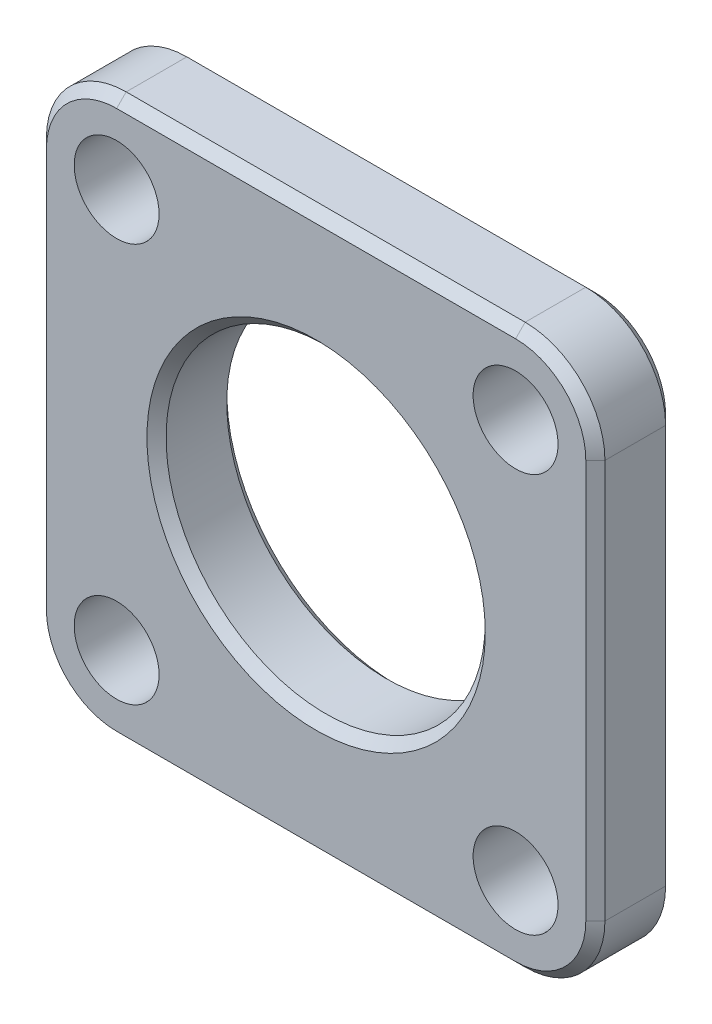
SolidWorks part; units mm, degrees
material "AISI 1020"
ref_plane "Front Plane" through (0, 0, 0) normal (0, 0, 1) x (1, 0, 0)
ref_plane "Top Plane" through (0, 0, 0) normal (0, 1, 0) x (1, 0, 0)
ref_plane "Right Plane" through (0, 0, 0) normal (1, 0, 0) x (0, 0, -1)
sketch "Base Sketch" plane through (0, 0, 0) normal (0, 0, 1) x (1, 0, 0)
  line L1 (22.225, -22.225) -> (-22.225, -22.225)
  line L2 (22.225, -22.225) -> (22.225, 22.225)
  line L3 (22.225, 22.225) -> (-22.225, 22.225)
  line L4 (-22.225, -22.225) -> (-22.225, 22.225)
  line L5 (22.225, -22.225) -> (-22.225, 22.225) construction
  line L6 (22.225, 22.225) -> (-22.225, -22.225) construction
  circle A0 centre (0, 0) radius 12.7
  point P0 (0, 0)
  dimension "D3" = 25.4
  dimension "D1" = 44.45
  dimension "D2" = 44.45
extrude "Base Extrude" add sketch "Base Sketch" against normal blind 6.35
fillet "Corner Fillet" radius 6.35 4 edges at (-22.225, -22.225, -3.175) (-22.225, 22.225, -3.175) (22.225, -22.225, -3.175) (22.225, 22.225, -3.175)
chamfer "Peripheral Chamfer" distance 0.762 angle 45 18 edges at (20.3651, -20.3651, -6.35) (22.225, 0, -6.35) (20.3651, 20.3651, -6.35) (0, 22.225, -6.35) (-20.3651, 20.3651, -6.35) (-22.225, 0, -6.35) (-20.3651, -20.3651, -6.35) (0, -22.225, -6.35) (12.7, 0, -6.35) (-20.3651, 20.3651, 0) (0, 22.225, 0) (20.3651, 20.3651, 0) (22.225, 0, 0) (20.3651, -20.3651, 0) (0, -22.225, 0) (-20.3651, -20.3651, 0) (-22.225, 0, 0) (12.7, 0, 0)
sketch "Corner Sketch" plane through (0, 0, 0) normal (0, 0, 1) x (1, 0, 0)
  line L0 (-21.463, 0) -> (21.463, 0) construction
  line L1 (-21.463, 15.875) -> (-21.463, -15.875) construction
  line L2 (21.463, -15.875) -> (21.463, 15.875) construction
  line L3 (0, 21.463) -> (0, -21.463) construction
  line L4 (15.875, 21.463) -> (-15.875, 21.463) construction
  line L5 (-15.875, -21.463) -> (15.875, -21.463) construction
  circle A0 centre (-15.875, 15.875) radius 3.3782
  circle A1 centre (-15.875, -15.875) radius 3.3782
  circle A2 centre (15.875, -15.875) radius 3.3782
  circle A3 centre (15.875, 15.875) radius 3.3782
  dimension "D1" = 6.7564
extrude "Corner Cut" cut sketch "Corner Sketch" against normal through all contours A3 | A2 | A1 | A0
